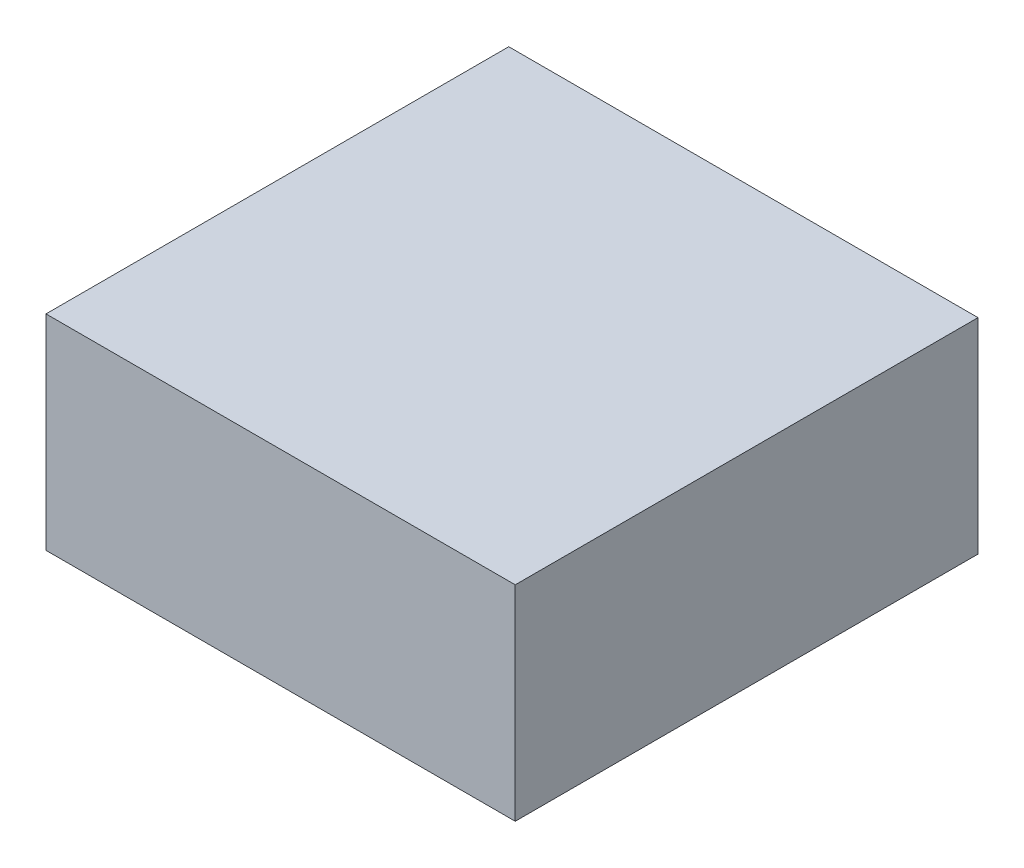
SolidWorks part; units mm, degrees
ref_plane "Front Plane" through (0, 0, 0) normal (0, 0, 1) x (1, 0, 0)
ref_plane "Top Plane" through (0, 0, 0) normal (0, 1, 0) x (1, 0, 0)
ref_plane "Right Plane" through (0, 0, 0) normal (1, 0, 0) x (0, 0, -1)
sketch "Sketch1" plane through (0, 0, 0) normal (0, 1, 0) x (1, 0, 0)
  line L1 (-181, -178.5) -> (181, -178.5)
  line L2 (-181, -178.5) -> (-181, 178.5)
  line L3 (-181, 178.5) -> (181, 178.5)
  line L4 (181, -178.5) -> (181, 178.5)
  line L5 (-181, -178.5) -> (181, 178.5) construction
  line L6 (-181, 178.5) -> (181, -178.5) construction
  point P0 (0, 0)
  dimension "D1" = 357
  dimension "D2" = 362
extrude "Boss-Extrude1" add sketch "Sketch1" along normal blind 158
